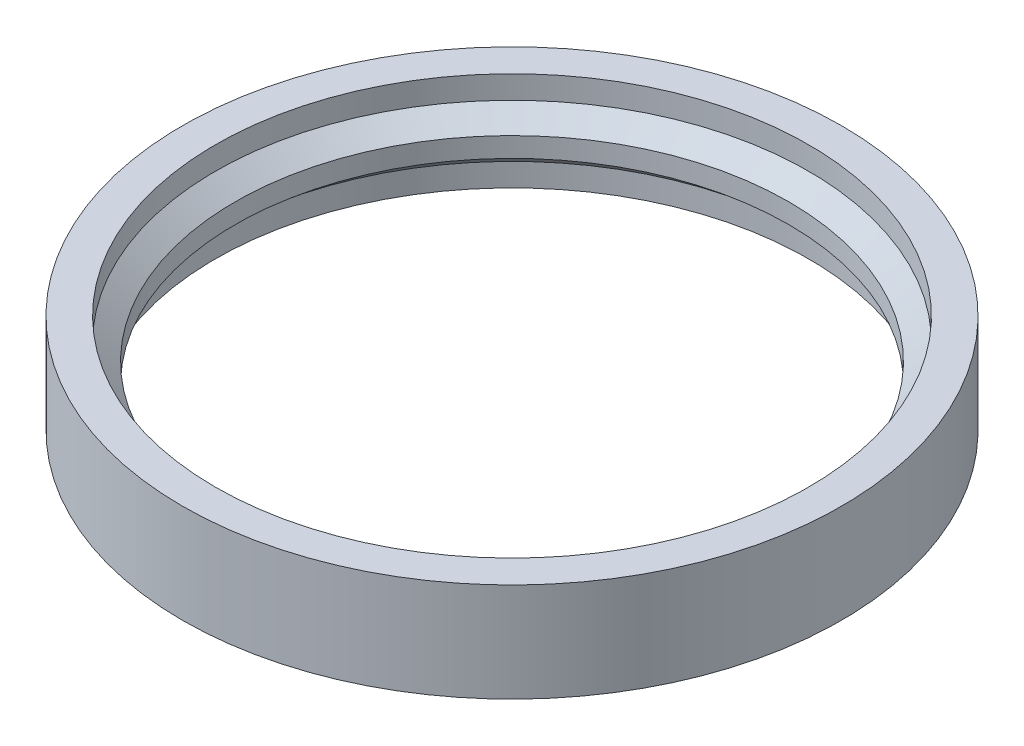
SolidWorks part; units mm, degrees
ref_plane "Alzado" through (0, 0, 0) normal (0, 0, 1) x (1, 0, 0)
ref_plane "Planta" through (0, 0, 0) normal (0, 1, 0) x (1, 0, 0)
ref_plane "Vista lateral" through (0, 0, 0) normal (1, 0, 0) x (0, 0, -1)
sketch "Croquis1" plane through (0, 0, 0) normal (0, 1, 0) x (1, 0, 0)
  circle A0 centre (0, 0) radius 42
  circle A1 centre (0, 0) radius 50
  dimension "D1" = 84
  dimension "D2" = 100
extrude "Saliente-Extruir1" add sketch "Croquis1" along normal blind 15
ref_plane "Plano2" through (0, 0, 0) normal (0, 0, 1) x (1, 0, 0)
sketch "Croquis3" plane through (0, 0, 0) normal (0, 0, 1) x (1, 0, 0)
  line L0 (-42, 0) -> (-42, 15)
  line L1 (-42, 0) -> (42, 0) construction
  line L2 (-45, 0) -> (45, 0) construction
  line L3 (42, 15) -> (-42, 15) construction
  line L4 (50, 15) -> (-50, 15) construction
  line L5 (-42, 15) -> (-45, 15)
  line L6 (45, 15) -> (-45, 15) construction
  line L7 (-45, 15) -> (-45, 11.5173)
  line L8 (45, 11.5173) -> (-45, 11.5173) construction
  line L9 (-45, 11.5173) -> (-42, 9)
  line L10 (42, 9) -> (-42, 9) construction
  line L11 (-33.8951, 7.5) -> (-50.1049, 7.5)
  line L12 (-42, 0) -> (-45, 0)
  line L13 (-45, 0) -> (-45, 3.4827)
  line L14 (-45, 3.4827) -> (-42, 6)
  point P22 (-42, 7.5)
ref_axis "Eje1" through (0, 3.8259, 0) along (0, -1, 0)
revolve "Cortar-Revolución1" cut sketch "Croquis3" angle 360 about axis through (0, 3.8259, 0) along (0, -1, 0)
